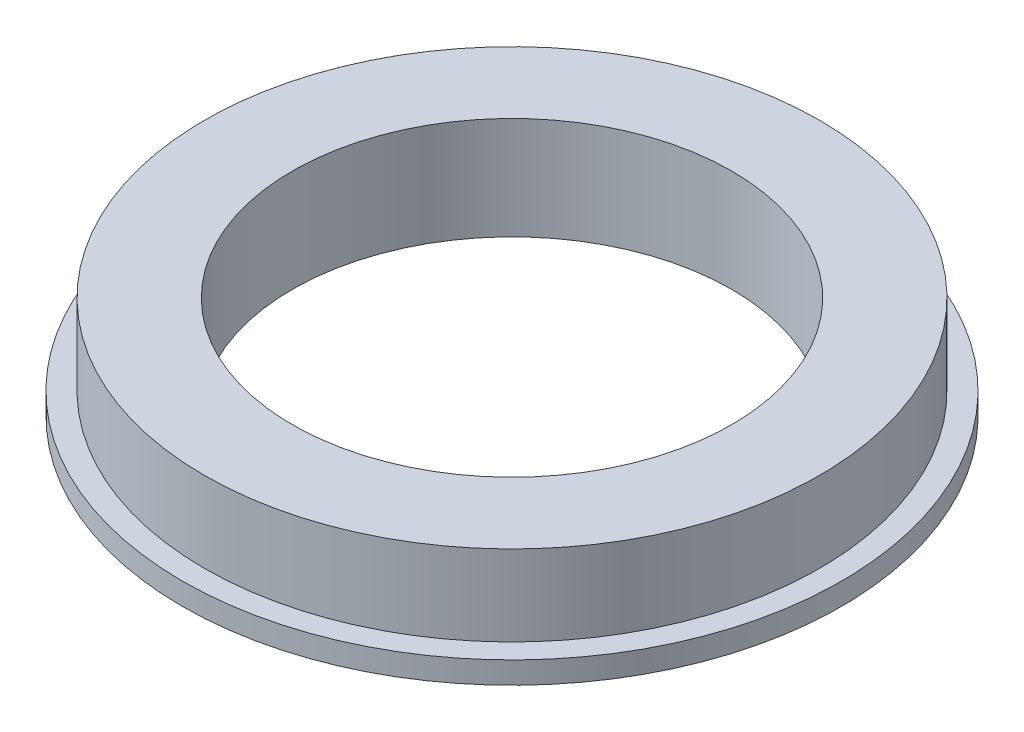
SolidWorks part; units mm, degrees
ref_plane "前视基准面" through (0, 0, 0) normal (0, 0, 1) x (1, 0, 0)
ref_plane "上视基准面" through (0, 0, 0) normal (0, 1, 0) x (1, 0, 0)
ref_plane "右视基准面" through (0, 0, 0) normal (1, 0, 0) x (0, 0, -1)
sketch "草图1" plane through (0, 0, 0) normal (0, 0, 1) x (1, 0, 0)
  line L0 (0, 0) -> (0, 17.8488) construction
  line L1 (-15, 0) -> (-15, 7)
  line L2 (-15, 7) -> (-21, 7)
  line L3 (-21, 7) -> (-21, 1.5)
  line L4 (-21, 1.5) -> (-22.5, 1.5)
  line L5 (-22.5, 1.5) -> (-22.5, 0)
  line L6 (-22.5, 0) -> (-15, 0)
  dimension "D1" = 30
  dimension "D2" = 42
  dimension "D3" = 7
  dimension "D4" = 45
  dimension "D5" = 1.5
revolve "旋转1" add sketch "草图1" angle 360 about L0
